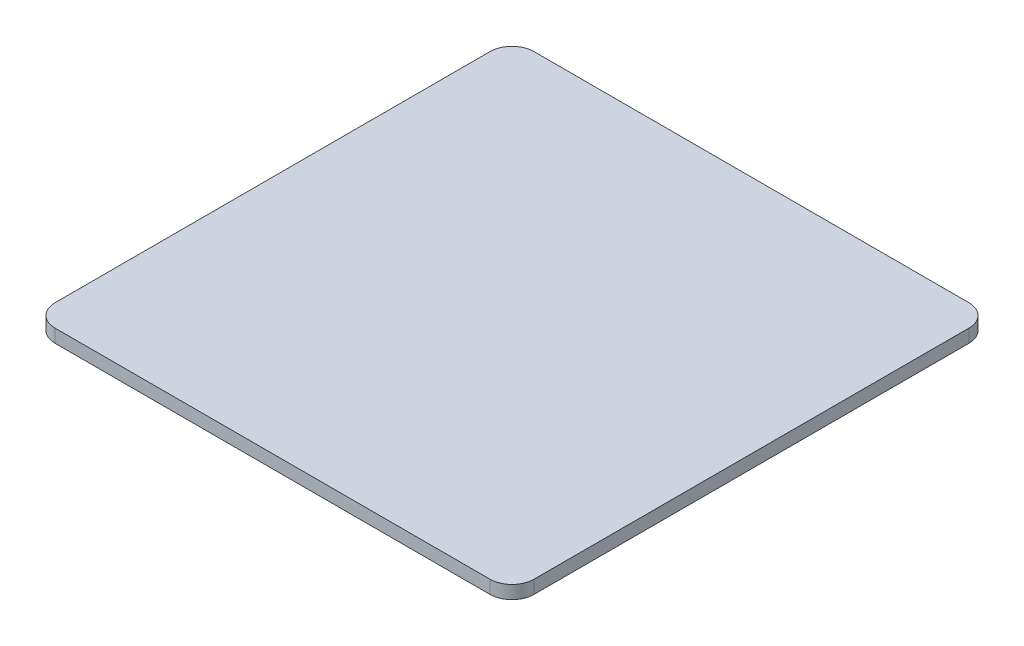
SolidWorks part; units mm, degrees
ref_plane "Front Plane" through (0, 0, 0) normal (0, 0, 1) x (1, 0, 0)
ref_plane "Top Plane" through (0, 0, 0) normal (0, 1, 0) x (1, 0, 0)
ref_plane "Right Plane" through (0, 0, 0) normal (1, 0, 0) x (0, 0, -1)
sketch "Esquisse1" plane through (0, 0, 0) normal (0, 1, 0) x (1, 0, 0)
  line L1 (10, 0) -> (208, 0)
  line L2 (0, 10) -> (0, 208)
  line L3 (10, 218) -> (208, 218)
  line L4 (218, 10) -> (218, 208)
  arc A0 (208, 0) -> (218, 10) centre (208, 10) ccw
  arc A1 (10, 0) -> (0, 10) centre (10, 10) cw
  arc A2 (208, 218) -> (218, 208) centre (208, 208) cw
  arc A3 (0, 208) -> (10, 218) centre (10, 208) cw
  point P9 (0, 0)
  point P14 (0, 218)
  dimension "D2" = 10
  dimension "D1" = 218
extrude "Boss.-Extru.1" add sketch "Esquisse1" along normal blind 6
